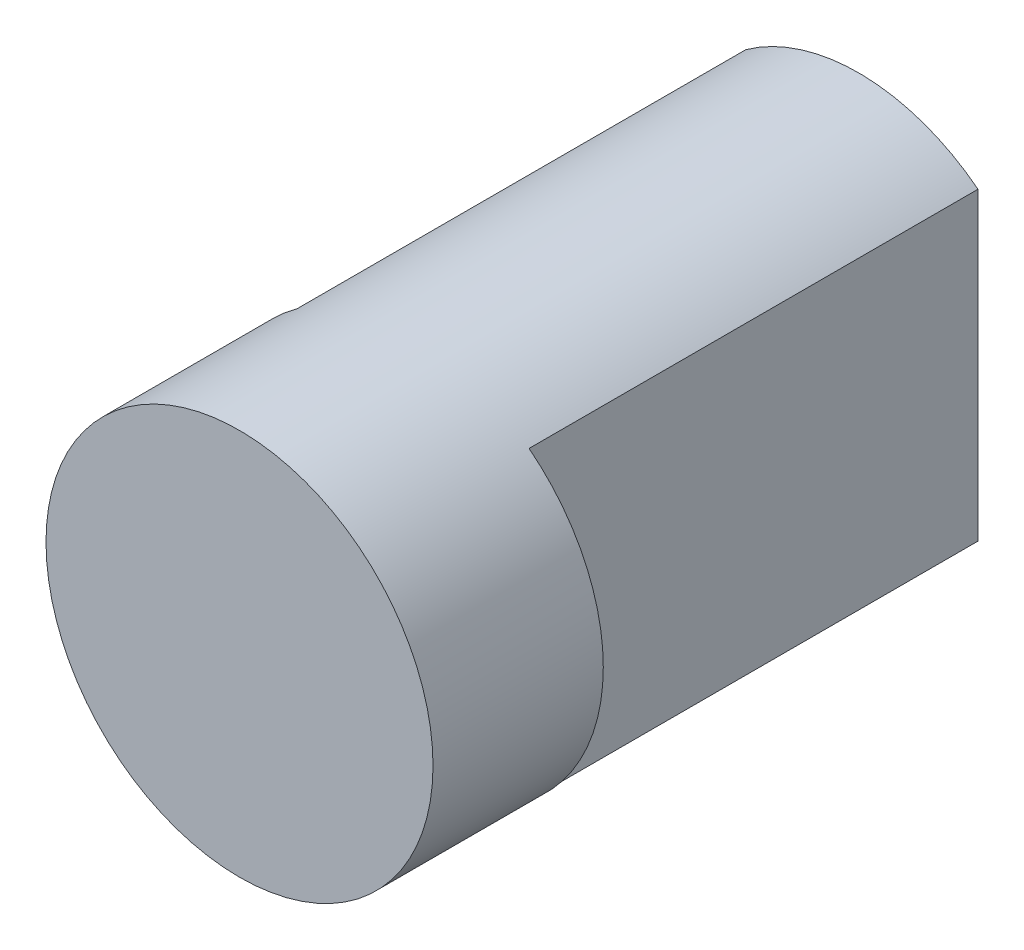
SolidWorks part; units mm, degrees
material "黄铜"
ref_plane "前视基准面" through (0, 0, 0) normal (0, 0, 1) x (1, 0, 0)
ref_plane "上视基准面" through (0, 0, 0) normal (0, 1, 0) x (1, 0, 0)
ref_plane "右视基准面" through (0, 0, 0) normal (1, 0, 0) x (0, 0, -1)
other "Configuration Table"
sketch "草图2" plane through (0, 0, 4.3852) normal (0, 0, -1) x (-1, 0, 0)
  circle A0 centre (-50.0235, 46.5026) radius 2.5
  dimension "D1" = 5
extrude "凸台-拉伸1" add sketch "草图2" along normal blind 8
sketch "草图3" plane through (0, 0, -3.6148) normal (0, 0, -1) x (-1, 0, 0)
  line L0 (-51.5645, 48.4711) -> (-51.5645, 44.534)
  line L1 (-48.5645, 48.5327) -> (-48.5645, 44.4725)
  arc A0 (-48.5645, 44.4725) -> (-48.5645, 48.5327) centre (-50.0235, 46.5026) ccw
  circle A1 centre (-50.0235, 46.5026) radius 2.5
  arc A2 (-51.5645, 48.4711) -> (-51.5645, 44.534) centre (-50.0235, 46.5026) ccw
  dimension "D2" = 3
  dimension "D1" = 0
extrude "切除-拉伸1" cut sketch "草图3" against normal blind 5.8
